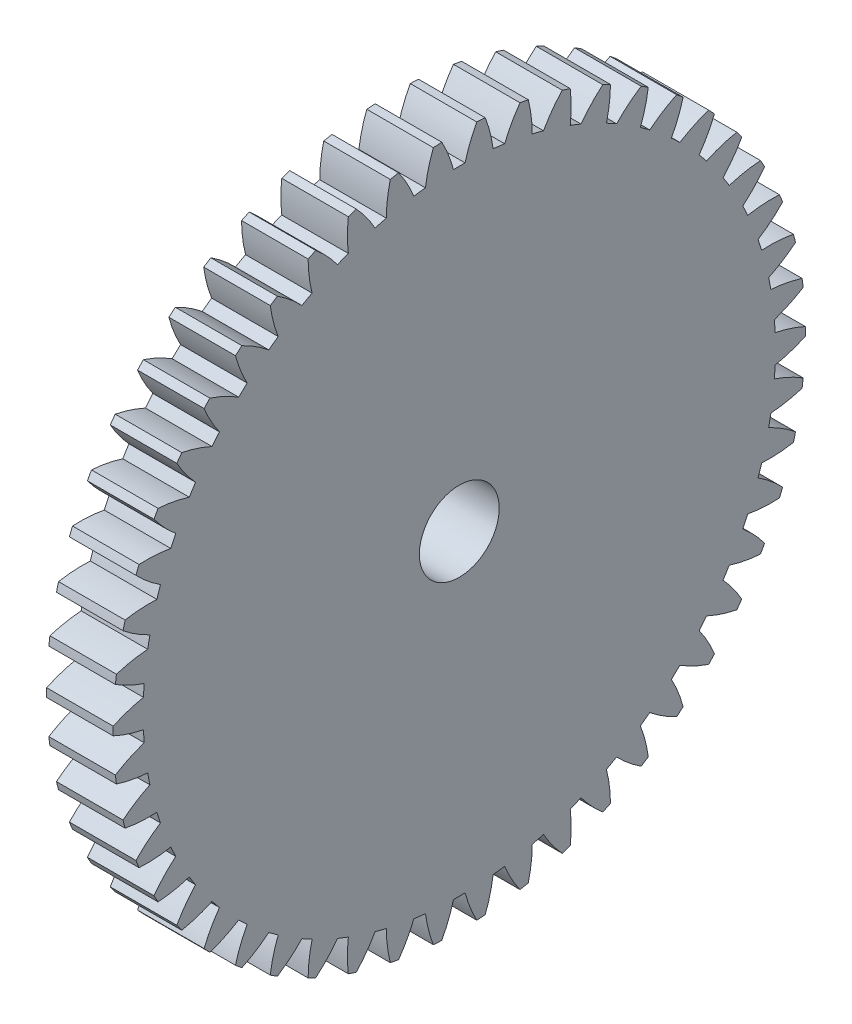
SolidWorks part; units mm, degrees
material "PVC 0.007 Plasticized"
ref_plane "Plane1" through (0, 0, 0) normal (0, 0, 1) x (1, 0, 0)
ref_plane "Plane2" through (0, 0, 0) normal (0, 1, 0) x (1, 0, 0)
ref_plane "Plane3" through (0, 0, 0) normal (1, 0, 0) x (0, 0, -1)
sketch "HoldingSke" plane through (0, 0, 0) normal (0, 1, 0) x (1, 0, 0)
  line L0 (0, 0) -> (1.2856, -1.5321)
  line L1 (-15, 0) -> (100, 0) construction
  line L2 (0, 0) -> (-2.1039, 2.3779)
  line L3 (0, 0) -> (-11.863, 4.5341)
  line L4 (0, 0) -> (5.5511, 6.6156)
  line L5 (0, 0) -> (-6.0902, -2.2715)
  line L6 (0, 0) -> (-2.0724, -1.3983)
  line L7 (-2.1039, 2.3779) -> (-0.7048, 8.7256)
  line L8 (-76.2, 54.61) -> (-75.7, 54.61)
  line L9 (-71.009, 38.7566) -> (-53.1078, 45.2721)
  line L10 (-76.2, 71.12) -> (104.1128, 71.12)
  line L11 (0, 0) -> (-2.5, 0)
  line L12 (-76.2, 101.6) -> (-76.181, 101.6)
  line L13 (24.9733, 27.94) -> (52.9518, 28.4284)
  line L14 (24.9733, 27.94) -> (24.9743, 27.94)
  line L15 (24.9733, 27.94) -> (100.4006, 29.5858)
  line L16 (-63.627, -0.5) -> (-12.827, -0.5)
  circle A0 centre (0, 0) radius 1.5
  circle A1 centre (0, 0) radius 3
  circle A2 centre (0, 0) radius 3
  circle A3 centre (0, 0) radius 1.5
  dimension "MHD" = 6
  dimension "Hub_dia" = 6
  dimension "Bore" = 3
  dimension "MBD" = 3
  dimension "Num_teeth" = 50
  dimension "Pitch" = 2
  dimension "Overall_len" = 6.5
  dimension "Show_teeth" = 50
  dimension "Thickness" = 2.5
  dimension "OAL" = 6.5001
  dimension "T_dim" = 0.5
  dimension "Ap" = 20
  dimension "H" = 19.05
  dimension "Pitch_radius" = 180.3128
  dimension "Width" = 2.5
  dimension "Backlash" = 0.019
  dimension "Addendum_fac" = 1
  dimension "Dedendum_fac" = 1.25
  dimension "Clearance_fac" = 0.25
  dimension "Dedendum_add" = 0.001
  dimension "Module" = 0.5
sketch "BasProSke" plane through (0, 0, 0) normal (0, 1, 0) x (1, 0, 0)
  line L0 (-10, 0) -> (60, 0) construction
  line L1 (0, 0) -> (0, 13)
  line L2 (0, 0) -> (2.5, 0)
  line L3 (2.5, 0) -> (2.5, 13)
  line L4 (2.5, 13) -> (0, 13)
  dimension "Thickness" = 2.5
  dimension "Diameter" = 26
revolve "Base-Revolve" add sketch "BasProSke" angle 360 about L0
sketch "TooCutSke" plane through (0, 0, 0) normal (1, 0, 0) x (0, 0, -1)
  line L1 (0, 0) -> (0, 107) construction
  line L2 (0, 0) -> (-0.4259, 12.4927) construction
  line L3 (0, 0) -> (-1.5691, 24.9404) construction
  line L4 (-0.4259, 12.4927) -> (-0.7846, 12.4702) construction
  arc A0 (0.2187, 11.872) -> (-0.2187, 11.872) centre (0, 0) ccw
  arc A1 (0.6715, 13.0081) -> (-0.6715, 13.0081) centre (0, 0) ccw
  circle A2 centre (0, 0) radius 12.5 construction
  circle A3 centre (0, 0) radius 11.7462 construction
  arc A4 (-0.2187, 11.872) -> (-0.6715, 13.0081) centre (-5.0549, 10.6028) ccw
  arc A5 (0.6715, 13.0081) -> (0.2187, 11.872) centre (5.0549, 10.6028) ccw
  dimension "Root_dia" = 23.748
  dimension "Overcut_dia" = 26.0508
  dimension "Pitch_dia" = 25
  dimension "Base_dia" = 23.4923
  dimension "Flank_rad" = 5
  dimension "Half_ang" = 3.6
  dimension "Half_CT" = 0.3594
extrude "ToothCut" cut sketch "TooCutSke" along normal through all
fillet "Breaks" [suppressed] radius 0.01
fillet "RootFillets" [suppressed] radius 0.126
pattern_circular "TeethCuts" count 50 over 360 about axis through (0, 0, 0) along (1, 0, 0) of "ToothCut", "RootFillets", "Breaks"
sketch "HubNeaOneSke" plane through (0, 0, 0) normal (-1, 0, 0) x (0, 0, 1)
  circle A0 centre (0, 0) radius 3
  dimension "Diameter" = 6
extrude "HubNearOne" add sketch "HubNeaOneSke" along normal blind 4.0001
sketch "HubNeaBotSke" plane through (0, 0, 0) normal (-1, 0, 0) x (0, 0, 1)
  circle A0 centre (0, 0) radius 3
  dimension "Diameter" = 6
extrude "HubNearBoth" [suppressed] add sketch "HubNeaBotSke" along normal blind 2
ref_plane "FarPln" through (2.5, 0, 0) normal (1, 0, 0) x (0, 0, -1)
sketch "HubFarSke" plane through (2.5, 0, 0) normal (1, 0, 0) x (0, 0, -1)
  circle A0 centre (0, 0) radius 3
  dimension "Diameter" = 6
extrude "HubFar" [suppressed] add sketch "HubFarSke" along normal blind 2
sketch "BorSke" plane through (0, 0, 0) normal (1, 0, 0) x (0, 0, -1)
  circle A0 centre (0, 0) radius 1.5
  dimension "Diameter" = 3
extrude "Bore" cut sketch "BorSke" along normal mid plane 13.0001
sketch "KeySke" plane through (0, 0, 0) normal (1, 0, 0) x (0, 0, -1)
  line L0 (-0.6, 0) -> (-0.6, 2)
  line L1 (-0.6, 2) -> (0.6, 2)
  line L2 (0.6, 2) -> (0.6, 0)
  line L3 (0, 0) -> (0, 34) construction
  line L4 (-0.6, 0) -> (0.6, 0)
  dimension "Offset" = 2
  dimension "Width" = 1.2
extrude "Keyway" [suppressed] cut sketch "KeySke" along normal mid plane 13.0001
pattern_circular "Keyway2" [suppressed] count 2 every 90 about axis through (-10, 0, 0) along (1, 0, 0)
sketch "Sketch1" plane through (-4.0001, 0, 0) normal (-1, 0, 0) x (0, 0, 1)
  line L0 (0, 0) -> (0, 1.8486) construction
  line L1 (0, 1.8486) -> (0, 3) construction
  line L2 (-0.4102, 2.4286) -> (0.4102, 2.4286) construction
  arc A0 (0.2187, 1.8466) -> (-0.2187, 1.8466) centre (0, -10.0583) ccw
  circle A4 centre (0, 0) radius 3 construction
  arc A5 (0.7389, 2.9076) -> (0.5452, 2.7366) centre (0.8435, 2.5938) ccw
  arc A6 (0.7389, 2.9076) -> (-0.7389, 2.9076) centre (0, 0) ccw
  arc A7 (0.5452, 2.7366) -> (0.2187, 1.8466) centre (5.055, 0.5775) ccw
  arc A8 (-0.5452, 2.7366) -> (-0.2187, 1.8466) centre (-5.055, 0.5775) cw
  arc A9 (-0.7389, 2.9076) -> (-0.5452, 2.7366) centre (-0.8435, 2.5938) cw
  point P5 (0, 2.4286)
  dimension "D5" = 11.9069
extrude "Cut-Extrude1" cut sketch "Sketch1" against normal up to surface (4.0001 mm away) up to face at (0, 0, -3)
pattern_circular "CirPattern2" count 10 over 360 about axis through (0, 0, 0) along (1, 0, 0) of "Cut-Extrude1"
equation "' \"Module@HoldingSke\" = 6.35"
equation "' \"Num_teeth@HoldingSke\" = 12"
equation "' \"Ap@HoldingSke\" =  20"
equation "' \"Ap@HoldingSke\" = 20"
equation "' \"Width@HoldingSke\" = 0.5 * 25.4"
equation "' \"Hub_dia@HoldingSke\"= 1 * 25.4"
equation "' \"Hub_dia@HoldingSke\" = 1 * 25.4"
equation "' \"Overall_len@HoldingSke\" = 1.0 * 25.4"
equation "' \"Bore@HoldingSke\" = 0.75 * 25.4"
equation "' \"T_dim@HoldingSke\" = 0.1 * 25.4"
equation "' \"Width@KeySke\" = 0.25 * 25.4"
equation "' \"Show_teeth@HoldingSke\" = 13"
equation "' \"Backlash@HoldingSke\" = 0.009 * 25.4"
equation "' \"Addendum_fac@HoldingSke\" = 1.0"
equation "' \"Dedendum_fac@HoldingSke\" = 1.25"
equation "' \"Dedendum_add@HoldingSke\" = 0.00005 * 25.4"
equation "' \"Clearance_fac@HoldingSke\" = 0.25"
equation "\"Pitch@HoldingSke\" = 1 / \"Module@HoldingSke\""
equation "\"Overcut_dia@TooCutSke\" = (\"Num_teeth@HoldingSke\" + 2 * \"Addendum_fac@HoldingSke\") / \"Pitch@HoldingSke\" + 0.002 * 25.4"
equation "\"Pitch_dia@TooCutSke\" = \"Num_teeth@HoldingSke\" / \"Pitch@HoldingSke\""
equation "\"Base_dia@TooCutSke\" = \"Num_teeth@HoldingSke\" / \"Pitch@HoldingSke\" * cos((\"Ap@HoldingSke\"  * 3.14159265 / 180))"
equation "\"Root_dia@TooCutSke\" = (\"Num_teeth@HoldingSke\" + 2) / \"Pitch@HoldingSke\" - 2 * (\"Addendum_fac@HoldingSke\" + \"Dedendum_fac@HoldingSke\") / \"Pitch@HoldingSke\" - \"Dedendum_add@HoldingSke\" * 2"
equation "\"Half_ang@TooCutSke\" = 180 / \"Num_teeth@HoldingSke\""
equation "\"Half_CT@TooCutSke\" = \"Num_teeth@HoldingSke\" / \"Pitch@HoldingSke\" * sin((3.14159265 / 2 / \"Num_teeth@HoldingSke\")) / 2 - 7 * \"Backlash@HoldingSke\" / 4"
equation "\"Flank_rad@TooCutSke\" = \"Num_teeth@HoldingSke\" / \"Pitch@HoldingSke\" / 5"
equation "\"Radius@RootFillets\" = \"Clearance_fac@HoldingSke\" / \"Pitch@HoldingSke\" + \"Dedendum_add@HoldingSke\""
equation "\"Break_rad@Breaks\" = 0.02 / \"Pitch@HoldingSke\""
equation "\"Thickness@HoldingSke\" = \"Width@HoldingSke\""
equation "\"OAL@HoldingSke\" = \"Thickness@HoldingSke\""
equation "\"MHD@HoldingSke\" = (\"Num_teeth@HoldingSke\" + 2) / \"Pitch@HoldingSke\" - 2 * (\"Addendum_fac@HoldingSke\" + \"Dedendum_fac@HoldingSke\")  / \"Pitch@HoldingSke\" - \"Dedendum_add@HoldingSke\" * 2"
equation "\"MBD@HoldingSke\" = (\"Num_teeth@HoldingSke\" + 2) / \"Pitch@HoldingSke\" - 2 * (\"Addendum_fac@HoldingSke\" + \"Dedendum_fac@HoldingSke\")  / \"Pitch@HoldingSke\" - \"Dedendum_add@HoldingSke\" * 2 - 0.002 * 25.4"
equation "\"MHD@HoldingSke\" = ((sgn( \"MHD@HoldingSke\" - \"Hub_dia@HoldingSke\" )-1)*( \"MHD@HoldingSke\" - \"Hub_dia@HoldingSke\" ))/-2+ \"Hub_dia@HoldingSke\""
equation "\"MBD@HoldingSke\" = ((sgn( \"MBD@HoldingSke\" - \"Bore@HoldingSke\" )-1)*( \"MBD@HoldingSke\" - \"Bore@HoldingSke\" ))/-2+ \"Bore@HoldingSke\""
equation "\"OAL@HoldingSke\" = ((sgn( \"OAL@HoldingSke\" - \"Overall_len@HoldingSke\" )+1)*( \"OAL@HoldingSke\" - \"Overall_len@HoldingSke\" ))/2 + \"Overall_len@HoldingSke\" + 0.000002 * 25.4"
equation "\"Num_teeth@TeethCuts\" = int( \"Show_teeth@HoldingSke\" ) + 1"
equation "\"Num_teeth@TeethCuts\" = ((sgn( \"Num_teeth@TeethCuts\" - \"Num_teeth@HoldingSke\" )-1)*( \"Num_teeth@TeethCuts\" - \"Num_teeth@HoldingSke\" ))/-2+ \"Num_teeth@HoldingSke\""
equation "\"Num_teeth@TeethCuts\" = ((sgn( \"Num_teeth@TeethCuts\" - 2.0)+1)*( \"Num_teeth@TeethCuts\" - 2.0))/2 +2.0"
equation "\"Angle@TeethCuts\" = 360.0 / \"Num_teeth@HoldingSke\""
equation "\"Diameter@BasProSke\" = (\"Num_teeth@HoldingSke\" + 2 * \"Addendum_fac@HoldingSke\") / \"Pitch@HoldingSke\""
equation "\"Thickness@BasProSke\"  = \"Thickness@HoldingSke\""
equation "' \"Fillet_rad@BasProSke\" =  \"Thickness@HoldingSke\" * 0.05"
equation "' \"Fillet_rad@BasProSke\" = \"Thickness@HoldingSke\" * 0.05"
equation "\"MHD@HoldingSke\" = ((sgn( \"MHD@HoldingSke\" - \"Root_dia@TooCutSke\" )-1)*( \"MHD@HoldingSke\" - \"Root_dia@TooCutSke\" ))/-2+ \"Root_dia@TooCutSke\""
equation "\"Diameter@HubNeaOneSke\" = \"MHD@HoldingSke\""
equation "\"Length@HubNearOne\" = \"OAL@HoldingSke\" - \"Thickness@BasProSke\""
equation "\"Diameter@HubNeaBotSke\" = \"MHD@HoldingSke\""
equation "\"Length@HubNearBoth\" = ( \"OAL@HoldingSke\" - \"Thickness@BasProSke\" ) / 2.0"
equation "\"Thickness@FarPln\" = \"Thickness@BasProSke\""
equation "\"Diameter@HubFarSke\" = \"MHD@HoldingSke\""
equation "\"Length@HubFar\" = ( \"OAL@HoldingSke\" - \"Thickness@BasProSke\" ) / 2.0"
equation "\"Diameter@BorSke\" = \"MBD@HoldingSke\""
equation "\"D1@Bore\" = \"OAL@HoldingSke\" * 2.0"
equation "\"D1@Keyway\" = \"OAL@HoldingSke\" * 2.0"
equation "\"Offset@KeySke\" = \"T_dim@HoldingSke\" + \"MBD@HoldingSke\" / 2.0"
